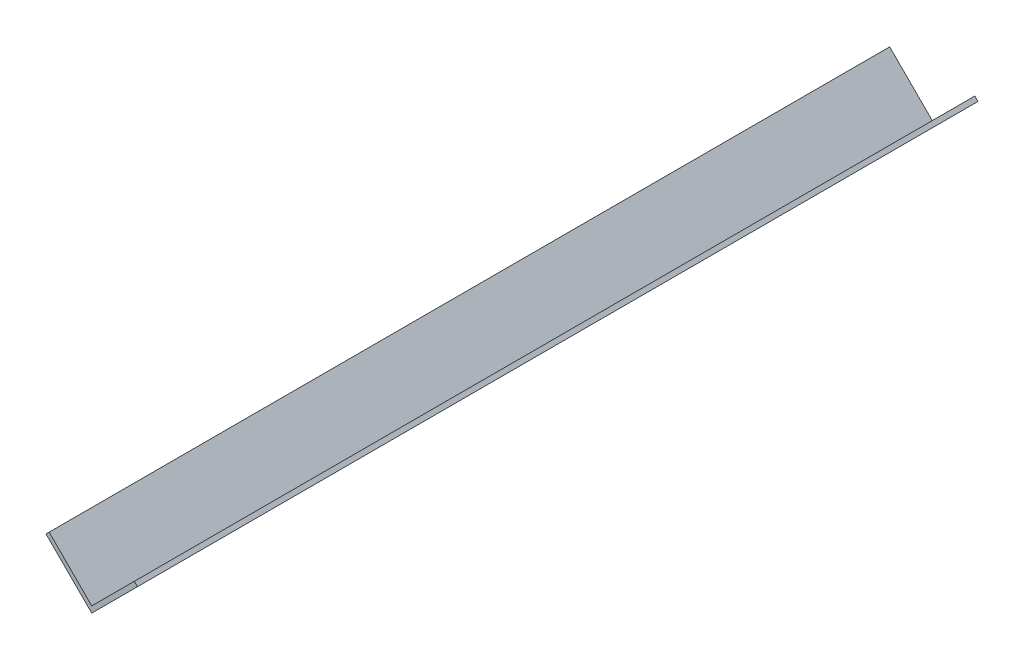
SolidWorks part; units mm, degrees
material "6061-T6 (SS)"
ref_plane "Front Plane" through (0, 0, 0) normal (0, 0, 1) x (1, 0, 0)
ref_plane "Top Plane" through (0, 0, 0) normal (0, 1, 0) x (1, 0, 0)
ref_plane "Right Plane" through (0, 0, 0) normal (1, 0, 0) x (0, 0, -1)
sketch "Sketch1" plane through (0, 0, 0) normal (0, 0, 1) x (1, 0, 0)
  line L0 (0, 0) -> (-17.9605, 17.9605)
  line L1 (-17.9605, 17.9605) -> (-16.7257, 19.1953)
  line L2 (-16.7257, 19.1953) -> (0, 2.4696)
  line L3 (0, 2.4696) -> (16.7257, 19.1953)
  line L4 (16.7257, 19.1953) -> (17.9605, 17.9605)
  line L5 (17.9605, 17.9605) -> (0, 0)
  dimension "D1" = 1.7463
  dimension "D2" = 25.4
extrude "Boss-Extrude1" add sketch "Sketch1" along normal blind 330.2
